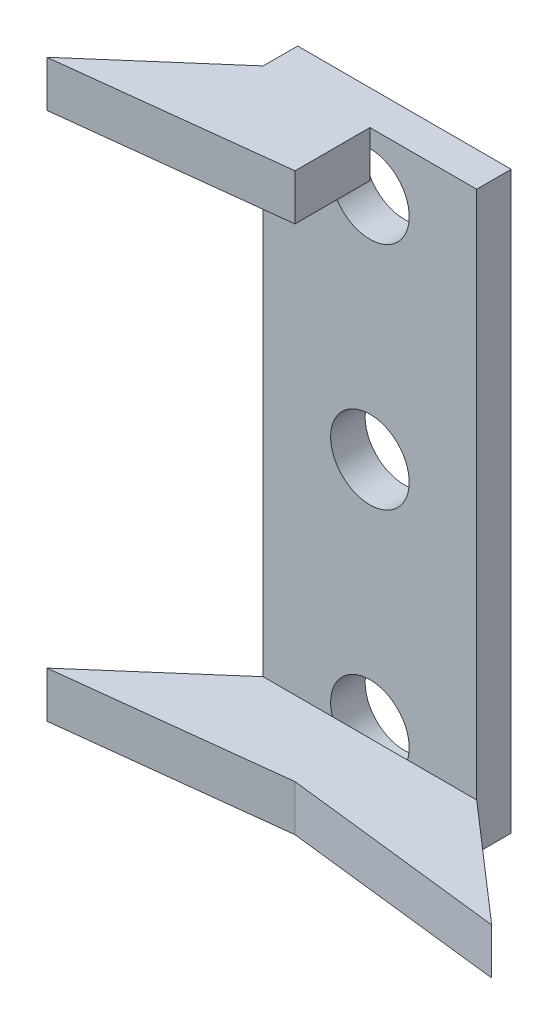
SolidWorks part; units mm, degrees
ref_plane "Front Plane" through (0, 0, 0) normal (0, 0, 1) x (1, 0, 0)
ref_plane "Top Plane" through (0, 0, 0) normal (0, 1, 0) x (1, 0, 0)
ref_plane "Right Plane" through (0, 0, 0) normal (1, 0, 0) x (0, 0, -1)
sketch "Sketch1" plane through (0, 0, 0) normal (0, 1, 0) x (1, 0, 0)
  line L0 (-46.4226, 32.5772) -> (-147.0048, -54.9741)
  line L1 (-46.4226, 32.5772) -> (46.4226, 32.5772)
  line L4 (46.4226, 32.5772) -> (46.4226, -32.5772)
  line L7 (-147.0048, -54.9741) -> (46.4226, -32.5772)
  point P0 (0, 0)
extrude "Boss-Extrude1" add sketch "Sketch1" along normal blind 40
mirror "Mirror1" about plane through (46.4226, 40, -32.5772) normal (-1, 0, 0) of "Boss-Extrude1"
sketch "Sketch3" plane through (0, 0, -32.5772) normal (0, 0, -1) x (-1, 0, 0)
  line L1 (46.4226, 0) -> (-139.2677, 0)
  line L2 (46.4226, 0) -> (46.4226, 500)
  line L3 (46.4226, 500) -> (-139.2677, 500)
  line L4 (-139.2677, 0) -> (-139.2677, 500)
  dimension "D1" = 500
extrude "Boss-Extrude2" add sketch "Sketch3" along normal blind 30
ref_plane "Plane1" through (0, 250, 0) normal (0, 1, 0) x (1, 0, 0)
mirror "Mirror5" about plane through (0, 250, 0) normal (0, 1, 0) of "Boss-Extrude1"
sketch "Sketch4" plane through (0, 0, -62.5772) normal (0, 0, -1) x (-1, 0, 0)
  circle A0 centre (-46.4226, 250) radius 34.176
extrude "Cut-Extrude1" cut sketch "Sketch4" against normal blind 30
pattern_linear "LPattern1" count 2 spacing 200 along (0, 1, 0) count 2 spacing 200 along (0, -1, 0) of "Cut-Extrude1"
